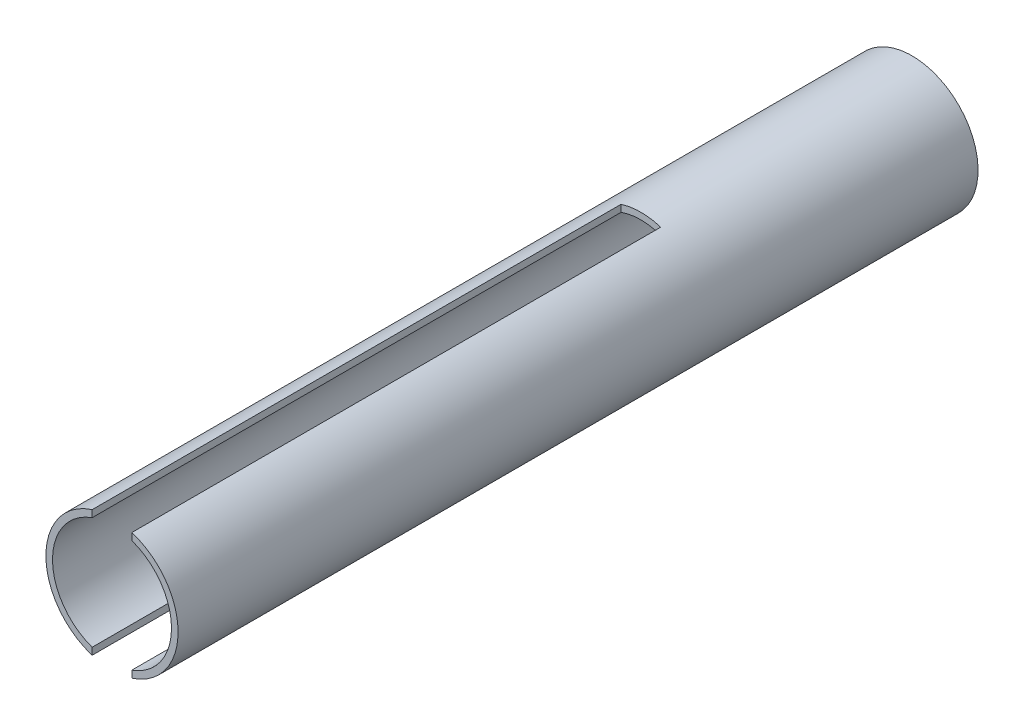
SolidWorks part; units mm, degrees
ref_plane "Front" through (0, 0, 0) normal (0, 0, 1) x (1, 0, 0)
ref_plane "Top" through (0, 0, 0) normal (0, 1, 0) x (1, 0, 0)
ref_plane "Right" through (0, 0, 0) normal (1, 0, 0) x (0, 0, -1)
sketch "Sketch1" plane through (0, 0, 0) normal (0, 0, 1) x (1, 0, 0)
  circle A0 centre (0, 0) radius 25
  circle A1 centre (0, 0) radius 22.5
  dimension "D1" = 50
  dimension "D2" = 45
extrude "Boss-Extrude1" add sketch "Sketch1" against normal blind 300
sketch "Sketch2" plane through (0, 0, 0) normal (0, 0, 1) x (1, 0, 0)
  line L1 (-7.5, 19.3596) -> (7.5, 19.3596)
  line L2 (-7.5, 19.3596) -> (-7.5, 26.6404)
  line L3 (-7.5, 26.6404) -> (7.5, 26.6404)
  line L4 (7.5, 19.3596) -> (7.5, 26.6404)
  line L5 (-7.5, 19.3596) -> (7.5, 26.6404) construction
  line L6 (-7.5, 26.6404) -> (7.5, 19.3596) construction
  point P0 (0, 23)
  dimension "D1" = 7.2807
  dimension "D2" = 15
  dimension "D3" = 23
extrude "Cut-Extrude1" cut sketch "Sketch2" against normal blind 200
mirror "Mirror1" about plane through (0, 0, 0) normal (0, 1, 0) of "Cut-Extrude1"
sketch "Sketch3" plane through (0, 0, -300) normal (0, 0, -1) x (-1, 0, 0)
  circle A0 centre (0, 0) radius 25
  dimension "D1" = 50
extrude "Boss-Extrude2" add sketch "Sketch3" along normal blind 2.5
